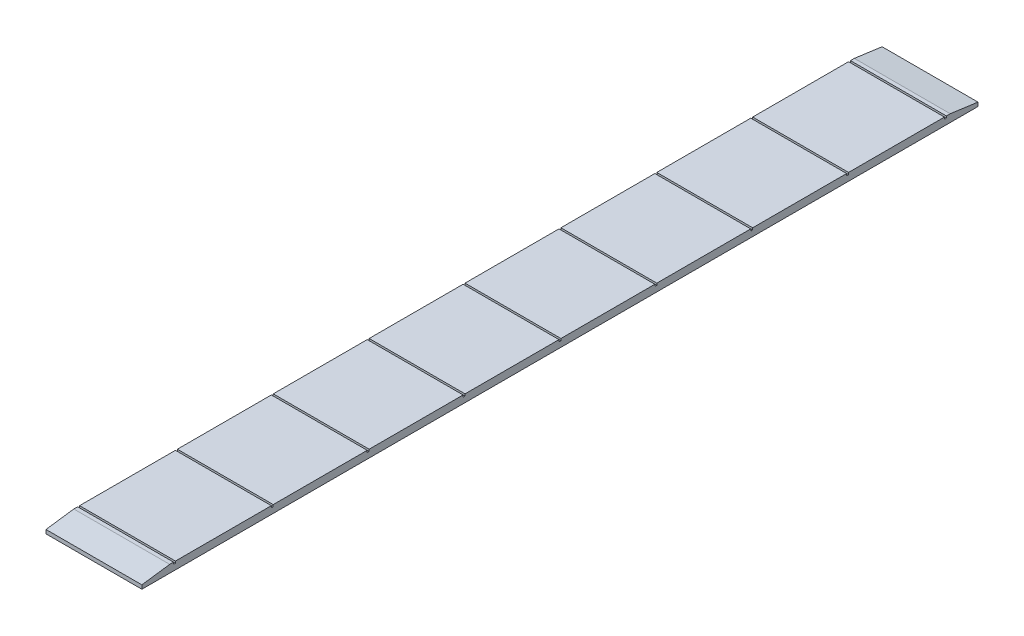
SolidWorks part; units mm, degrees
ref_plane "Front Plane" through (0, 0, 0) normal (0, 0, 1) x (1, 0, 0)
ref_plane "Top Plane" through (0, 0, 0) normal (0, 1, 0) x (1, 0, 0)
ref_plane "Right Plane" through (0, 0, 0) normal (1, 0, 0) x (0, 0, -1)
sketch "Sketch1" plane through (0, 0, 0) normal (0, 1, 0) x (1, 0, 0)
  line L1 (0, 0) -> (25, 0)
  line L2 (0, 0) -> (0, -220)
  line L3 (0, -220) -> (25, -220)
  line L4 (25, 0) -> (25, -220)
  dimension "D1" = 25
  dimension "D2" = 220
extrude "Boss-Extrude1" add sketch "Sketch1" along normal blind 2
sketch "Sketch2" plane through (0, 2, 0) normal (0, 1, 0) x (1, 0, 0)
  line L0 (25, -220) -> (25, 0) construction
  line L1 (25, -9.25) -> (0, -9.25)
  line L2 (25, -9.25) -> (25, -9.75)
  line L3 (25, -9.75) -> (0, -9.75)
  line L4 (0, -9.25) -> (0, -9.75)
  line L5 (0, 0) -> (0, -220) construction
  line L6 (25, 0) -> (0, 0) construction
  line L7 (0, -220) -> (25, -220) construction
  line L8 (25, -210.25) -> (0, -210.25)
  line L9 (25, -210.25) -> (25, -210.75)
  line L10 (25, -210.75) -> (0, -210.75)
  line L11 (0, -210.25) -> (0, -210.75)
  line L12 (25, -60.25) -> (0, -60.25)
  line L13 (25, -34.75) -> (0, -34.75)
  line L14 (25, -34.75) -> (25, -35.25)
  line L15 (25, -35.25) -> (0, -35.25)
  line L16 (0, -34.75) -> (0, -35.25)
  line L17 (25, -59.75) -> (0, -59.75)
  line L18 (0, -59.75) -> (0, -60.25)
  line L19 (25, -59.75) -> (25, -60.25)
  line L20 (25, -85.25) -> (0, -85.25)
  line L21 (25, -84.75) -> (0, -84.75)
  line L22 (0, -84.75) -> (0, -85.25)
  line L23 (25, -84.75) -> (25, -85.25)
  line L24 (25, -110.25) -> (0, -110.25)
  line L25 (25, -109.75) -> (0, -109.75)
  line L26 (0, -109.75) -> (0, -110.25)
  line L27 (25, -109.75) -> (25, -110.25)
  line L28 (25, -135.25) -> (0, -135.25)
  line L29 (25, -134.75) -> (0, -134.75)
  line L30 (0, -134.75) -> (0, -135.25)
  line L31 (25, -134.75) -> (25, -135.25)
  line L32 (25, -160.25) -> (0, -160.25)
  line L33 (25, -159.75) -> (0, -159.75)
  line L34 (0, -159.75) -> (0, -160.25)
  line L35 (25, -159.75) -> (25, -160.25)
  line L36 (25, -185.25) -> (0, -185.25)
  line L37 (25, -184.75) -> (0, -184.75)
  line L38 (0, -184.75) -> (0, -185.25)
  line L39 (25, -184.75) -> (25, -185.25)
  line L40 (25, -35.25) -> (25, -60.25) construction
  dimension "D1" = 0.5
  dimension "D2" = 9.25
  dimension "D3" = 0.5
  dimension "D4" = 9.25
  dimension "D5" = 0.5
  dimension "D6" = 25
  dimension "D8" = 25
  dimension "D9" = 25
  dimension "D7" = 7
extrude "Cut-Extrude1" cut sketch "Sketch2" against normal blind 0.5
sketch "Sketch3" plane through (0, 0, 0) normal (0, 0, -1) x (-1, 0, 0)
  line L1 (-25, 2) -> (0, 2)
  line L2 (-25, 2) -> (-25, 0)
  line L3 (-25, 0) -> (0, 0)
  line L4 (0, 2) -> (0, 0)
extrude "Cut-Extrude2" cut sketch "Sketch3" against normal blind 1
sketch "Sketch4" plane through (0, 0, 220) normal (0, 0, 1) x (1, 0, 0)
  line L1 (0, 2) -> (25, 2)
  line L2 (0, 2) -> (0, 0)
  line L3 (0, 0) -> (25, 0)
  line L4 (25, 2) -> (25, 0)
extrude "Cut-Extrude3" cut sketch "Sketch4" against normal blind 1
sketch "Sketch5" plane through (0, 0, 0) normal (-1, 0, 0) x (0, 0, 1)
  line L0 (1, 1) -> (8.25, 2)
  line L1 (1, 0) -> (1, 2) construction
  line L2 (1, 2) -> (9.25, 2) construction
  line L3 (8.25, 2) -> (1, 2)
  line L4 (1, 2) -> (1, 1)
  line L5 (1, 0) -> (219, 0) construction
  line L6 (211.75, 2) -> (219, 1)
  line L7 (210.75, 2) -> (219, 2) construction
  line L8 (219, 2) -> (219, 0) construction
  line L9 (219, 1) -> (219, 2)
  line L10 (219, 2) -> (211.75, 2)
  dimension "D1" = 1
  dimension "D2" = 1
  dimension "D3" = 1
  dimension "D4" = 1
extrude "Cut-Extrude4" cut sketch "Sketch5" against normal up to surface (25 mm away) up to face at (25, 1.675, 110)
sketch "Sketch6" plane through (0, 2, 0) normal (0, 1, 0) x (1, 0, 0)
  line L0 (25, -197.75) -> (0, -197.75)
  line L1 (25, -210.25) -> (25, -185.25) construction
  line L2 (0, -185.25) -> (0, -210.25) construction
